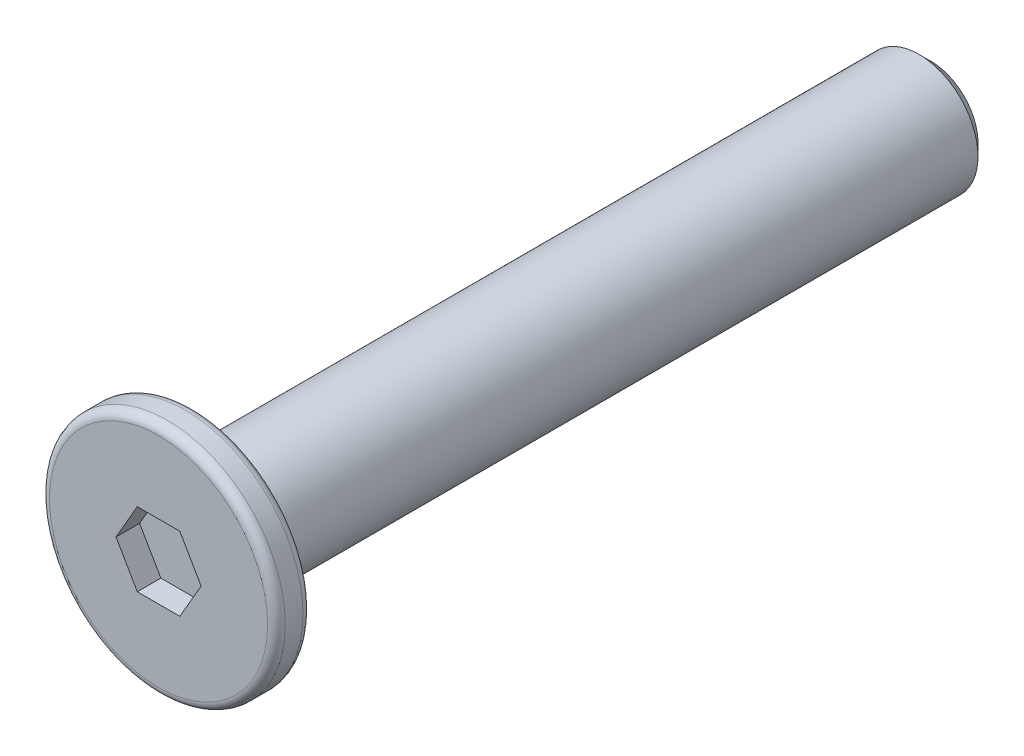
SolidWorks part; units mm, degrees
ref_plane "前视基准面" through (0, 0, 0) normal (0, 0, 1) x (1, 0, 0)
ref_plane "上视基准面" through (0, 0, 0) normal (0, 1, 0) x (1, 0, 0)
ref_plane "右视基准面" through (0, 0, 0) normal (1, 0, 0) x (0, 0, -1)
sketch "草图1" plane through (0, 0, 0) normal (0, 0, 1) x (1, 0, 0)
  circle A0 centre (0, 0) radius 4
  dimension "D1" = 8
extrude "凸台-拉伸1" add sketch "草图1" along normal mid plane 1.2
sketch "草图2" plane through (0, 0, -0.6) normal (0, 0, -1) x (-1, 0, 0)
  circle A0 centre (0, 0) radius 2
  dimension "D1" = 4
extrude "凸台-拉伸2" add sketch "草图2" along normal blind 25
chamfer "倒角1" distance 0.4 angle 45 1 edges at (-2, 0, -25.6)
sketch "草图3" plane through (0, 0, 0.6) normal (0, 0, 1) x (1, 0, 0)
  line L1 (1.4434, 0) -> (0.7217, 1.25)
  line L2 (0.7217, 1.25) -> (-0.7217, 1.25)
  line L3 (-0.7217, 1.25) -> (-1.4434, 0)
  line L4 (-1.4434, 0) -> (-0.7217, -1.25)
  line L5 (-0.7217, -1.25) -> (0.7217, -1.25)
  line L6 (0.7217, -1.25) -> (1.4434, 0)
  circle A0 centre (0, 0) radius 1.25 construction
  dimension "D1" = 2.5
extrude "切除-拉伸1" cut sketch "草图3" against normal blind 0.8
fillet "圆角2" radius 0.3 2 edges at (4, 0, -0.6) (4, 0, 0.6)
